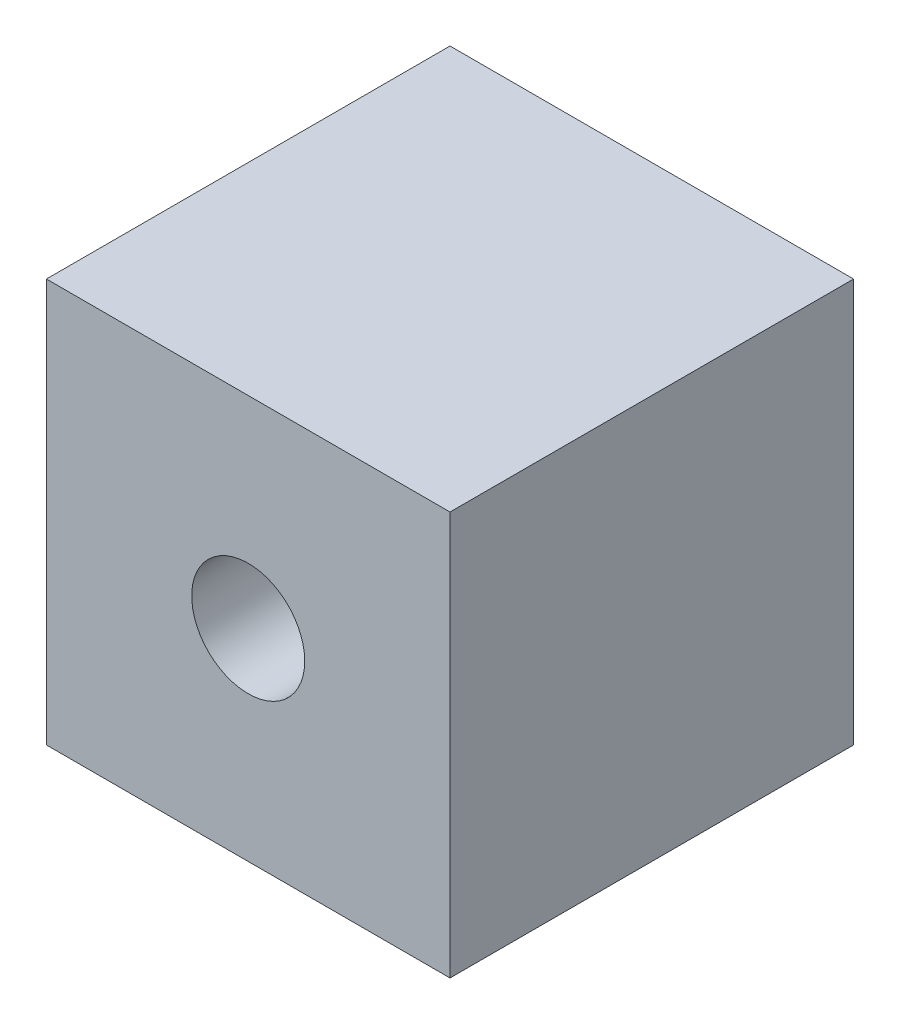
SolidWorks part; units mm, degrees
ref_plane "정면" through (0, 0, 0) normal (0, 0, 1) x (1, 0, 0)
ref_plane "윗면" through (0, 0, 0) normal (0, 1, 0) x (1, 0, 0)
ref_plane "우측면" through (0, 0, 0) normal (1, 0, 0) x (0, 0, -1)
sketch "스케치1" plane through (0, 0, 0) normal (0, 0, 1) x (1, 0, 0)
  line L1 (-5, 5) -> (5, 5)
  line L2 (-5, 5) -> (-5, -5)
  line L3 (-5, -5) -> (5, -5)
  line L4 (5, 5) -> (5, -5)
  line L5 (-5, 5) -> (5, -5) construction
  line L6 (-5, -5) -> (5, 5) construction
  circle A0 centre (0, 0) radius 1.4
  point P0 (0, 0)
  dimension "D2" = 2.8
  dimension "D1" = 10
  dimension "D3" = 10
extrude "보스-돌출1" add sketch "스케치1" along normal blind 10
